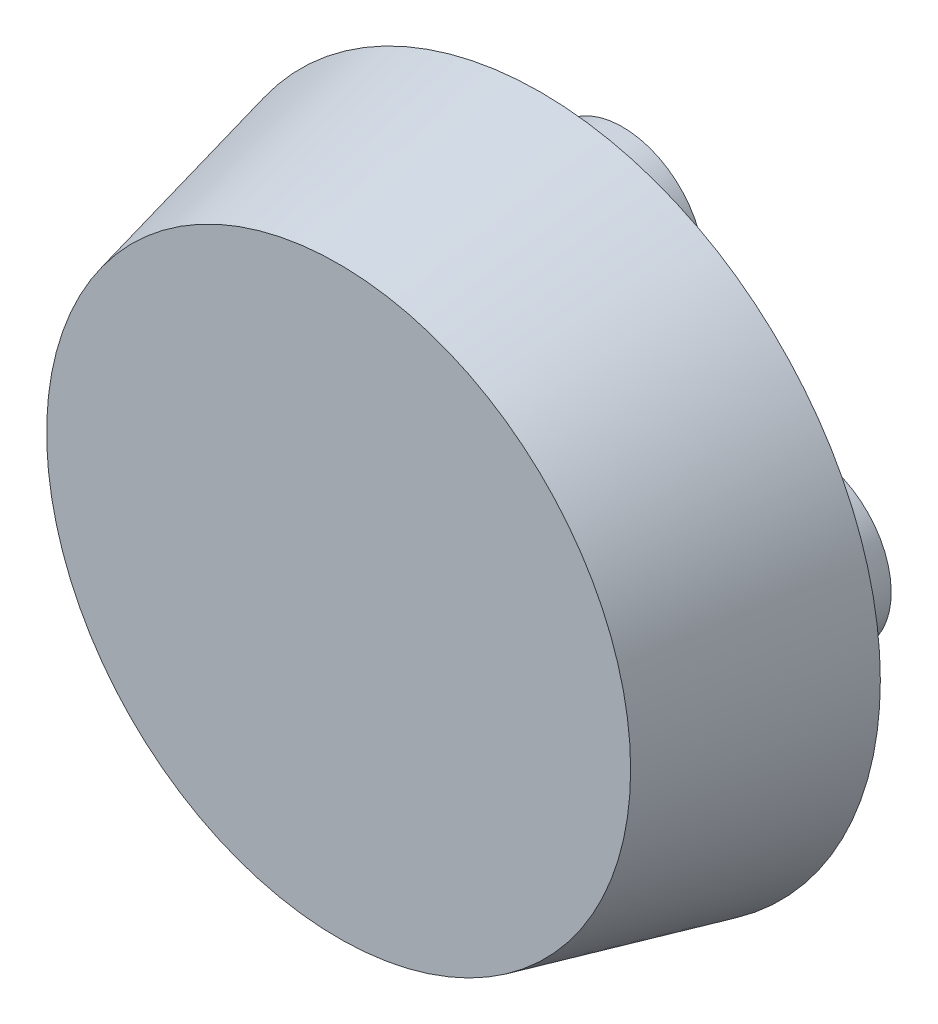
SolidWorks part; units mm, degrees
ref_plane "Front Plane" through (0, 0, 0) normal (0, 0, 1) x (1, 0, 0)
ref_plane "Top Plane" through (0, 0, 0) normal (0, 1, 0) x (1, 0, 0)
ref_plane "Right Plane" through (0, 0, 0) normal (1, 0, 0) x (0, 0, -1)
sketch "Big Plug Sketch" plane through (0, 0, 0) normal (1, 0, 0) x (0, 0, -1)
  line L0 (594.1751, -558.8643) -> (886.5863, -558.8643) construction
  line L1 (0, 0) -> (531.6016, 125) construction
  line L2 (0, 0) -> (531.6016, 0) construction
  line L3 (531.6016, 125) -> (531.6016, 0)
  line L4 (531.6016, 125) -> (618.1413, 145.3488)
  line L5 (531.6016, 0) -> (635, 0)
  arc A1 (635, 0) -> (618.1413, 145.3488) centre (0, 0) ccw
  dimension "D1" = 546.1
  dimension "D2" = 635
  dimension "D3" = 125
revolve "Big Plug" add sketch "Big Plug Sketch" angle 360 about L2
ref_plane "Big Plug Subsurface Plane" through (0, 0, -618.1413) normal (0, 0, 1) x (1, 0, 0)
sketch "Cable Sketch" plane through (0, 0, -618.1413) normal (0, 0, 1) x (1, 0, 0)
  line L0 (0, 80) -> (0, 0) construction
  circle A0 centre (0, 80) radius 35
  dimension "D1" = 70
  dimension "D2" = 80
extrude "Cable Extrude" add sketch "Cable Sketch" against normal blind 35
pattern_circular "Cable Pattern" count 4 over 360 about axis through (0, 0, 0) along (0, 0, 1) of "Cable Extrude"
